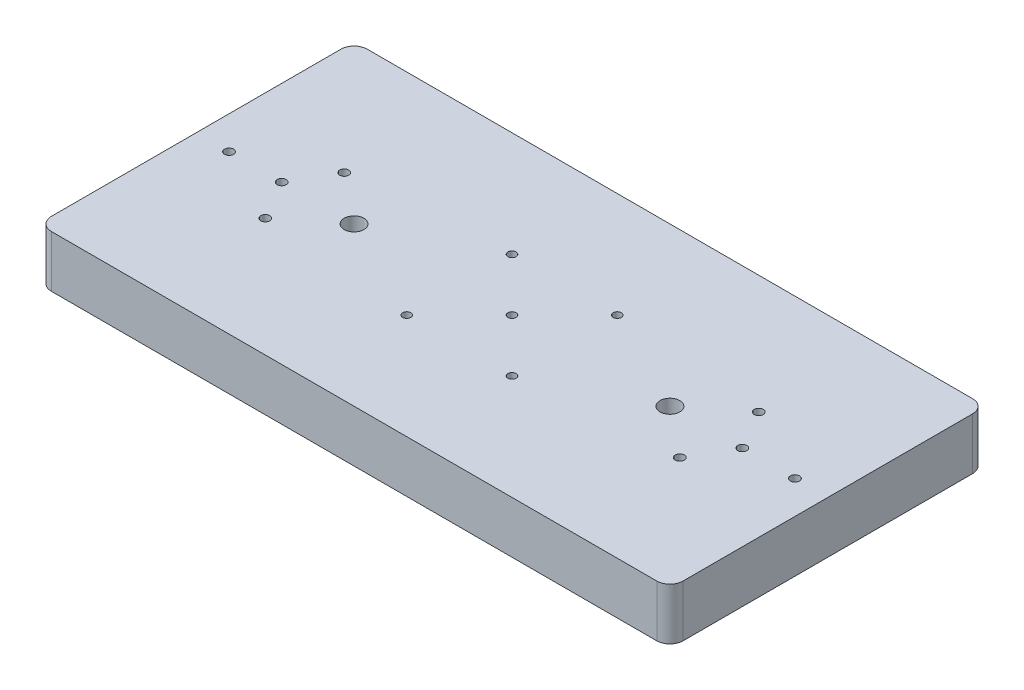
SolidWorks part; units mm, degrees
ref_plane "Front" through (0, 0, 0) normal (0, 0, 1) x (1, 0, 0)
ref_plane "Top" through (0, 0, 0) normal (0, 1, 0) x (1, 0, 0)
ref_plane "Right" through (0, 0, 0) normal (1, 0, 0) x (0, 0, -1)
sketch "Sketch1" plane through (0, 0, 0) normal (0, 1, 0) x (1, 0, 0)
  line L0 (-304.8, -152.4) -> (304.8, 152.4) construction
  line L1 (-304.8, 152.4) -> (304.8, 152.4)
  line L2 (-304.8, 152.4) -> (-304.8, -152.4)
  line L3 (-304.8, -152.4) -> (304.8, -152.4)
  line L4 (304.8, 152.4) -> (304.8, -152.4)
  dimension "D1" = 609.6
  dimension "D2" = 304.8
extrude "Extrude1" add sketch "Sketch1" along normal blind 50.0062
fillet "Fillet1" radius 12.7 4 edges at (304.8, 25.0031, 152.4) (304.8, 25.0031, -152.4) (-304.8, 25.0031, -152.4) (-304.8, 25.0031, 152.4)
sketch "Sketch2" plane through (0, 50.0062, 0) normal (0, 1, 0) x (-1, 0, 0)
  line L0 (292.1, 152.4) -> (-292.1, 152.4) construction
  line L1 (304.8, -139.7) -> (304.8, 139.7) construction
  circle A0 centre (152.4, 0) radius 9.525
  circle A1 centre (-152.4, 0) radius 9.525
  dimension "D1" = 304.8
  dimension "D2" = 19.05
  dimension "D4" = 152.4
  dimension "D5" = 152.4
  dimension "D3" = 152.4
extrude "Cut-Extrude1" cut sketch "Sketch2" against normal through all
hole_wizard "CBORE for 5/16 Socket Head Cap Screw1" positions "Sketch6" profile "Sketch5" counterbore size "5/16" standard "Ansi Inch" end condition through all
sketch "Sketch6" plane through (0, 0, 0) normal (0, -1, 0) x (1, 0, 0)
  point P0 (-200.025, 38.1)
  point P1 (-200.025, -38.1)
  point P3 (200.025, -38.1)
  point P5 (200.025, 38.1)
  point P12 (-222.25, 0)
  point P14 (-273.05, 0)
  point P16 (222.25, 0)
  point P18 (273.05, 0)
  dimension "D1" = 47.625
  dimension "D2" = 38.1
  dimension "D3" = 76.2
  dimension "D4" = 47.625
  dimension "D5" = 50.8
  dimension "D6" = 22.225
  dimension "D7" = 22.225
  dimension "D8" = 50.8
sketch "Sketch5" plane through (-200.025, 0, 38.1) normal (1, 0, 0) x (0, 0, -1)
  line L0 (0, 0) -> (0, 50.0062)
  line L1 (0, 50.0062) -> (4.365, 50.0062)
  line L3 (4.365, 50.0062) -> (4.365, 8.6995)
  line L4 (4.365, 8.6995) -> (6.7475, 8.6995)
  line L5 (6.7475, 8.6995) -> (6.7475, 0)
  line L7 (6.7475, 0) -> (0, 0)
  line L11 (0, -6.35) -> (0, 107.95) construction
  dimension "Thru Hole Dia." = 8.73
  dimension "Thru Hole Depth" = 50.0062
  dimension "C'Bore Dia." = 13.495
  dimension "C'Bore Depth" = 8.6995
hole_wizard "3/8-16 Tapped Hole1" positions "Sketch8" profile "Sketch7" tap size "3/8-16" standard "Ansi Inch"
sketch "Sketch8" plane through (0, 50.0062, 0) normal (0, 1, 0) x (-1, 0, 0)
  point P0 (50.8, 50.8)
  point P1 (50.8, -50.8)
  point P3 (-50.8, -50.8)
  point P5 (-50.8, 50.8)
  point P8 (0, 0)
  dimension "D1" = 50.8
  dimension "D2" = 101.6
  dimension "D3" = 50.8
  dimension "D4" = 101.6
sketch "Sketch7" plane through (-50.8, 50.0062, 50.8) normal (1, 0, 0) x (0, 0, 1)
  line L0 (0, 0) -> (0, 29.3722)
  line L1 (0, 29.3722) -> (3.9687, 26.9875)
  line L2 (3.9687, 26.9875) -> (3.9687, 0)
  line L5 (3.9687, 0) -> (0, 0)
  line L10 (0, 29.3722) -> (-3.9688, 26.9875) construction
  line L11 (0, -6.35) -> (0, 107.95) construction
  dimension "Tap Drill Dia." = 7.9375
  dimension "Tap Drill Depth" = 26.9875
  dimension "Drill Angle" = 118
cosmetic thread "Hole Thread1" parameters "D1"=19.05, "D2"=9.525
cosmetic thread "Hole Thread2" parameters "D1"=19.05, "D2"=9.525
cosmetic thread "Hole Thread3" parameters "D1"=19.05, "D2"=9.525
cosmetic thread "Hole Thread4" parameters "D1"=19.05, "D2"=9.525
cosmetic thread "Hole Thread5" parameters "D1"=19.05, "D2"=9.525
